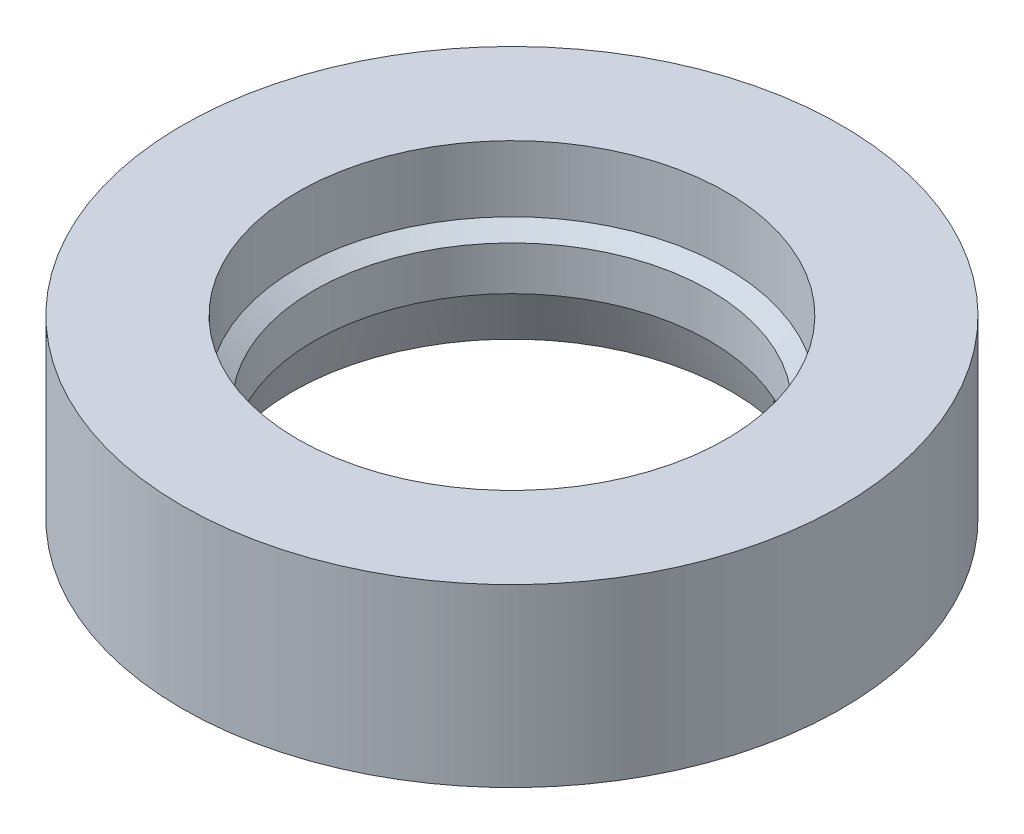
SolidWorks part; units mm, degrees
ref_plane "Front Plane" through (0, 0, 0) normal (0, 0, 1) x (1, 0, 0)
ref_plane "Top Plane" through (0, 0, 0) normal (0, 1, 0) x (1, 0, 0)
ref_plane "Right Plane" through (0, 0, 0) normal (1, 0, 0) x (0, 0, -1)
sketch "Sketch1" plane through (0, 0, 0) normal (1, 0, 0) x (0, 0, -1)
  line L0 (-6.0592, 3.6112) -> (-6.0592, -4.3888)
  line L1 (-6.0592, 3.6112) -> (-0.8092, 3.6112)
  line L2 (-3.0592, -4.3888) -> (-1.0592, -4.3888)
  line L6 (-0.8092, 0.6112) -> (-0.8092, 3.6112)
  line L10 (8.9408, 4.1112) -> (8.9408, -4.3888) construction
  line L11 (-3.0592, -4.3888) -> (-3.0592, -2.8886)
  line L12 (-3.0592, -2.8886) -> (-4.5592, -2.8888)
  line L13 (-0.0592, -1.8888) -> (-0.0592, 0.1112)
  line L14 (-0.8092, 0.6112) -> (-0.0592, 0.1112)
  line L15 (-0.0592, -1.8888) -> (-1.0592, -4.3888)
  line L16 (-4.5592, -2.8888) -> (-4.5592, -4.3888)
  line L17 (-4.5592, -4.3888) -> (-6.0592, -4.3888)
  point P13 (-3.1381, -4.282)
  point P14 (0, 0)
  point P15 (0, 0)
  point P16 (0, 0)
  point P17 (0, 0)
  point P18 (0, 0)
  point P19 (-4.9907, -4.151)
  point P20 (-4.9907, -4.3889)
  point P21 (-3.0592, -2.8888)
  point P22 (0, 0)
  point P23 (0, 0)
  dimension "D1" = 8
  dimension "D2" = 5.25
  dimension "D3" = 5
  dimension "D4" = 3
  dimension "D5" = 15
  dimension "D6" = 1.5
  dimension "D7" = 1.5
  dimension "D8" = 2
  dimension "D9" = 2
revolve "Revolve1" add sketch "Sketch1" angle 360 about L10
ref_plane "Plane1" through (0, 5.926, -14.8148) normal (0, -0.3714, 0.9285) x (1, 0, 0)
sketch "Sketch10" plane through (0, 5.926, -14.8148) normal (0, -0.3714, 0.9285) x (1, 0, 0)
  circle A0 centre (4.0417, -9.017) radius 0.75
  point P2 (0, 0)
  point P3 (0, 0)
  point P4 (0, 0)
  point P5 (0, 0)
  dimension "D1" = 1.5
extrude "Cut-Extrude2" cut sketch "Sketch10" against normal through all both and the other way through all
